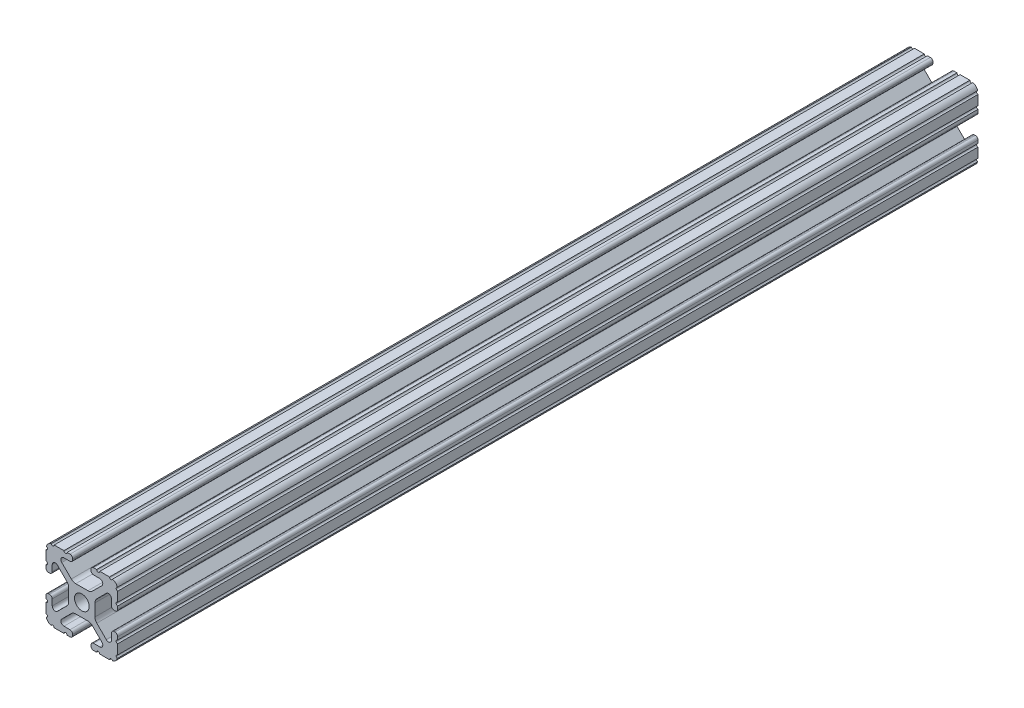
SolidWorks part; units mm, degrees
ref_plane "Front Plane" through (0, 0, 0) normal (0, 0, 1) x (1, 0, 0)
ref_plane "Top Plane" through (0, 0, 0) normal (0, 1, 0) x (1, 0, 0)
ref_plane "Right Plane" through (0, 0, 0) normal (1, 0, 0) x (0, 0, -1)
sketch "Sketch2" plane through (0, 0, 0) normal (0, 0, 1) x (1, 0, 0)
  line L0 (0, 12.7) -> (0, -12.7) construction
  line L1 (-12.7, 0) -> (12.7, 0) construction
  line L2 (3.2512, -12.7) -> (12.7, -12.7)
  line L3 (12.7, -12.7) -> (12.7, -3.2512)
  line L4 (3.2512, -12.7) -> (3.2512, -10.4902)
  line L5 (3.2512, -10.4902) -> (8.9276, -10.4902)
  line L6 (8.9276, -10.4902) -> (3.0856, -4.6482)
  line L7 (0, 0) -> (12.7, -12.7) construction
  line L8 (12.7, -3.2512) -> (10.4902, -3.2512)
  line L9 (10.4902, -3.2512) -> (10.4902, -8.9276)
  line L10 (10.4902, -8.9276) -> (4.6482, -3.0856)
  circle A0 centre (0, 0) radius 2.6035
  arc A1 (6.3485, -10.4902) -> (7.1039, -8.6665) centre (6.3485, -9.4219) ccw construction
  point P8 (0, -4.6482)
  dimension "Center Hole Diameter" = 5.207
  dimension "Rail Height" = 25.4
  dimension "Rail Width" = 25.4
  dimension "T-Slot Width" = 6.5024
  dimension "Slot Inner Width" = 14.8336
  dimension "Thickness" = 2.2098
  dimension "Slot Depth" = 5.842
  dimension "D1" = 2.2098
sketch "Sketch3" plane through (0, 0, 0) normal (1, 0, 0) x (0, 0, -1)
  line L0 (-228.6, -12.7) -> (228.6, -12.7) construction
  line L1 (-205.74, 0) -> (205.74, 0) construction
  dimension "Length" = 457.2
  dimension "D1" = 411.48
sketch "Sketch4" plane through (0, 0, 0) normal (0, 0, 1) x (1, 0, 0)
  line L0 (4.1904, -12.7) -> (10.1173, -12.7)
  line L1 (3.2512, -12.7) -> (12.7, -12.7) construction
  line L2 (3.2512, -12.7) -> (3.2512, -10.4902) construction
  line L3 (3.2512, -10.4902) -> (8.9276, -10.4902) construction
  line L4 (3.2512, -11.4294) -> (3.2512, -11.7608)
  line L5 (4.1904, -10.4902) -> (6.3485, -10.4902)
  line L6 (0, -4.6482) -> (2.164, -4.6482)
  line L7 (8.9276, -10.4902) -> (3.0856, -4.6482) construction
  line L8 (3.7373, -5.2999) -> (7.1039, -8.6665)
  line L9 (12.7, -12.7) -> (12.7, -3.2512) construction
  line L10 (10.4902, -8.9276) -> (4.6482, -3.0856) construction
  line L11 (10.4902, -3.2512) -> (10.4902, -8.9276) construction
  line L12 (10.4902, -6.3485) -> (10.4902, -4.1904)
  line L13 (12.7, -3.2512) -> (10.4902, -3.2512) construction
  line L14 (11.4294, -3.2512) -> (11.7608, -3.2512)
  line L15 (12.7, -4.1904) -> (12.7, -10.1173)
  line L16 (8.6665, -7.1039) -> (5.2999, -3.7373)
  line L17 (4.6482, 0) -> (4.6482, -2.164)
  line L18 (-12.7, 0) -> (12.7, 0) construction
  line L19 (0, -4.6482) -> (0, -2.6035)
  line L20 (0, 12.7) -> (0, -12.7) construction
  line L21 (4.6482, 0) -> (2.6035, 0)
  arc A0 (3.2512, -11.7608) -> (4.1904, -12.7) centre (4.1904, -11.7608) ccw
  arc A2 (3.2512, -11.4294) -> (4.1904, -10.4902) centre (4.1904, -11.4294) cw
  arc A3 (6.3485, -10.4902) -> (7.1039, -8.6665) centre (6.3485, -9.4219) ccw
  arc A4 (2.164, -4.6482) -> (3.7373, -5.2999) centre (2.164, -6.8732) cw
  arc A5 (10.1173, -12.7) -> (12.7, -10.1173) centre (10.1173, -10.1173) ccw
  arc A6 (8.6665, -7.1039) -> (10.4902, -6.3485) centre (9.4219, -6.3485) ccw
  arc A7 (10.4902, -4.1904) -> (11.4294, -3.2512) centre (11.4294, -4.1904) cw
  arc A8 (11.7608, -3.2512) -> (12.7, -4.1904) centre (11.7608, -4.1904) cw
  arc A9 (5.2999, -3.7373) -> (4.6482, -2.164) centre (6.8732, -2.164) cw
  circle A10 centre (0, 0) radius 2.6035 construction
  arc A11 (0, -2.6035) -> (2.6035, 0) centre (0, 0) ccw
  dimension "D1" = 2.5827
  dimension "D2" = 2.225
  dimension "D3" = 0.9392
extrude "Boss-Extrude1" add sketch "Sketch4" along normal mid plane 457.2
sketch "Sketch5" plane through (0, 0, 0) normal (0, 0, 1) x (1, 0, 0)
  line L0 (3.2512, -12.7) -> (12.7, -12.7) construction
  line L1 (4.1904, -10.4902) -> (6.3485, -10.4902) construction
  line L3 (0, 0) -> (12.7, -12.7) construction
  line L4 (6.3485, -10.4902) -> (6.3485, -12.7) construction
  line L5 (8.9276, -10.4902) -> (3.0856, -4.6482) construction
  circle A0 centre (10.3562, -12.7) radius 0.5524
  circle A1 centre (5.796, -12.7) radius 0.5524
  circle A2 centre (12.7, -10.3562) radius 0.5524
  circle A3 centre (12.7, -5.796) radius 0.5524
  point P10 (5.2694, -10.4902)
  point P12 (9.4219, -6.3485)
  dimension "D1" = 1.1049
extrude "Cut-Extrude1" cut sketch "Sketch5" against normal through all both and the other way through all
mirror "Mirror1" about plane through (0, 0, 0) normal (1, 0, 0) of bodies 137 134
mirror "Mirror2" about plane through (0, 0, 0) normal (0, 1, 0) of bodies 135
sketch "Sketch6" plane through (0, 0, -228.6) normal (0, 0, -1) x (-1, 0, 0)
  line L1 (-19.0187, 19.6542) -> (25.4816, 19.6542)
  line L2 (-19.0187, 19.6542) -> (-19.0187, -18.6104)
  line L3 (-19.0187, -18.6104) -> (25.4816, -18.6104)
  line L4 (25.4816, 19.6542) -> (25.4816, -18.6104)
extrude "Cut-Extrude2" cut sketch "Sketch6" against normal blind 152.4
equation "\"D1@Boss-Extrude1\"=\"Length@Sketch3\""
equation "\"D1@Sketch2\"=\"Thickness@Sketch2\""
equation "\"D2@Sketch4\"=\"Slot Inner Width@Sketch2\"*0.15"
equation "\"D1@Sketch4\"=\"D3@Sketch4\"*2.75"
equation "\"D3@Sketch4\"=\"Thickness@Sketch2\"*0.425"
equation "\"D1@Sketch5\"=\"Thickness@Sketch2\"*0.5"
equation "\"D1@Sketch3\"=\"Length@Sketch3\"*0.9"
